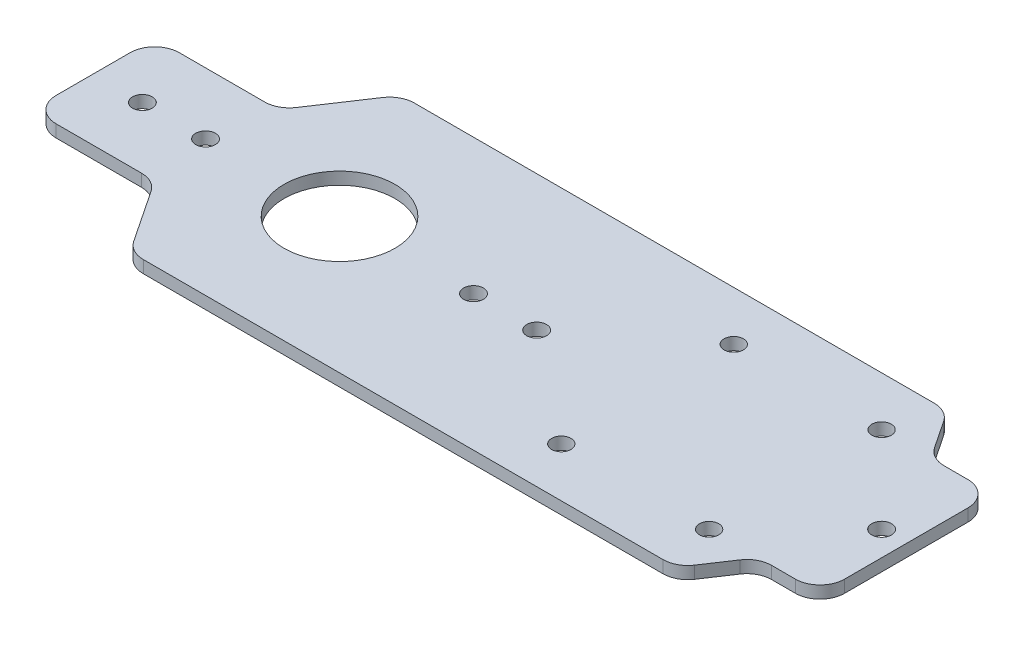
SolidWorks part; units mm, degrees
ref_plane "Front Plane" through (0, 0, 0) normal (0, 0, 1) x (1, 0, 0)
ref_plane "Top Plane" through (0, 0, 0) normal (0, 1, 0) x (1, 0, 0)
ref_plane "Right Plane" through (0, 0, 0) normal (1, 0, 0) x (0, 0, -1)
sketch "Sketch1" plane through (0, 0, 0) normal (0, 1, 0) x (1, 0, 0)
  line L0 (16.2686, 0) -> (85.3314, 0) construction
  line L1 (50.8, 0) -> (50.8, 3.1391) construction
  line L2 (19.05, 15.875) -> (31.75, 34.925)
  line L3 (-12.7, 15.875) -> (19.05, 15.875)
  line L4 (-12.7, 15.875) -> (-12.7, -15.875)
  line L5 (-12.7, -15.875) -> (19.05, -15.875)
  line L6 (114.3, 15.875) -> (114.3, -15.875)
  line L7 (-12.7, 15.875) -> (114.3, -15.875) construction
  line L8 (-12.7, -15.875) -> (114.3, 15.875) construction
  line L9 (31.75, 34.925) -> (69.85, 34.925)
  line L10 (69.85, 34.925) -> (82.55, 15.875)
  line L11 (50.8, 34.925) -> (50.8, 29.0511) construction
  line L12 (69.85, -34.925) -> (82.55, -15.875)
  line L13 (31.75, -34.925) -> (69.85, -34.925)
  line L14 (19.05, -15.875) -> (31.75, -34.925)
  line L15 (82.55, -15.875) -> (114.3, -15.875)
  line L16 (82.55, 15.875) -> (114.3, 15.875)
  circle A0 centre (0, 0) radius 2.54
  circle A1 centre (101.6, 0) radius 2.54
  circle A2 centre (16.2686, 0) radius 2.54 construction
  circle A3 centre (85.3314, 0) radius 2.54 construction
  dimension "D1" = 5.08
  dimension "D3" = 127
  dimension "D4" = 31.75
  dimension "D5" = 69.0628
  dimension "D2" = 101.6
  dimension "D6" = 19.05
  dimension "D7" = 31.75
  dimension "D8" = 38.1
extrude "Boss-Extrude1" add sketch "Sketch1" along normal blind 3.175
sketch "Sketch2" plane through (0, 3.175, 0) normal (0, 1, 0) x (1, 0, 0)
  circle A0 centre (50.8, 0) radius 14.2875
  circle A1 centre (0, 0) radius 2.54 construction
  dimension "D1" = 50.8
  dimension "D2" = 28.575
extrude "Cut-Extrude1" cut sketch "Sketch2" against normal blind 3.175
sketch "Sketch3" plane through (0, 3.175, 0) normal (0, 1, 0) x (1, 0, 0)
  line L0 (50.8, 0) -> (50.8, 14.2875) construction
  circle A2 centre (85.3314, 0) radius 2.54
  circle A3 centre (16.2686, 0) radius 2.54
  circle A5 centre (50.8, 0) radius 14.2875 construction
  circle A6 centre (50.8, 0) radius 14.2875 construction
  point P1 (0, 0)
  dimension "D2" = 5.08
  dimension "D3" = 5.08
  dimension "D4" = 69.0628
extrude "Cut-Extrude2" cut sketch "Sketch3" against normal through all
sketch "Sketch5" plane through (0, 0, 0) normal (0, -1, 0) x (1, 0, 0)
  line L5 (114.3, 15.875) -> (114.3, -15.875) construction
  line L10 (69.85, -34.925) -> (196.85, -34.925)
  line L11 (69.85, -34.925) -> (69.85, 34.925)
  line L12 (69.85, 34.925) -> (196.85, 34.925)
  line L13 (196.85, -34.925) -> (196.85, 34.925)
  line L14 (114.554, 17.272) -> (183.896, 17.272) construction
  line L15 (114.554, 17.272) -> (114.554, -17.272) construction
  line L16 (114.554, -17.272) -> (183.896, -17.272) construction
  line L17 (183.896, 17.272) -> (183.896, -17.272) construction
  line L18 (172.5083, 34.925) -> (180.975, 22.225)
  line L19 (172.5083, -34.925) -> (180.975, -22.225)
  line L20 (180.975, -22.225) -> (196.85, -22.225)
  line L21 (82.55, -15.875) -> (69.85, -34.925) construction
  line L22 (82.55, -15.875) -> (69.85, -34.925)
  line L23 (69.85, 34.925) -> (82.55, 15.875) construction
  line L24 (69.85, 34.925) -> (82.55, 15.875)
  line L25 (180.975, 22.225) -> (196.85, 22.225)
  circle A4 centre (101.6, 0) radius 2.54 construction
  circle A5 centre (85.3314, 0) radius 2.54 construction
  circle A6 centre (101.6, 0) radius 2.54
  circle A7 centre (85.3314, 0) radius 2.54
  circle A8 centre (130.175, 22.225) radius 2.4892
  circle A9 centre (168.275, 22.225) radius 2.4892
  circle A10 centre (130.175, -22.225) radius 2.4892
  circle A11 centre (168.275, -22.225) radius 2.4892
  circle A12 centre (190.5, 0) radius 2.54
  point P39 (0, 0)
  line M15 (69.85, -34.925) -> (82.55, -15.875)
  line M16 (82.55, -15.875) -> (114.3, -15.875)
  line M17 (114.3, -15.875) -> (114.3, 15.875)
  line M18 (114.3, 15.875) -> (82.55, 15.875)
  line M19 (82.55, 15.875) -> (69.85, 34.925)
  dimension "D2" = 4.9784
  dimension "D3" = 44.45
  dimension "D4" = 38.1
  dimension "D11" = 15.621
  dimension "D16" = 88.9
  dimension "D5" = 4.953
  dimension "D6" = 82.55
  dimension "D7" = 17.653
  dimension "D8" = 0.254
  dimension "D9" = 69.342
  dimension "D10" = 34.544
  dimension "D12" = 15.875
  dimension "D13" = 12.7
  dimension "D14" = 15.875
  dimension "D15" = 12.7
extrude "Boss-Extrude2" add sketch "Sketch5" against normal up to surface (3.175 mm away) contours L25 L18 L12 L10 L19 L20 L13 A11 A10 A9 A8 M19 M18 M17 M16 M15
fillet "Fillet1" radius 6.35 12 edges at (19.05, 1.5875, -15.875) (31.75, 1.5875, -34.925) (31.75, 1.5875, 34.925) (19.05, 1.5875, 15.875) (-12.7, 1.5875, -15.875) (-12.7, 1.5875, 15.875) (172.5083, 1.5875, -34.925) (180.975, 1.5875, -22.225) (196.85, 1.5875, -22.225) (196.85, 1.5875, 22.225) (180.975, 1.5875, 22.225) (172.5083, 1.5875, 34.925)
sketch "Sketch4"
